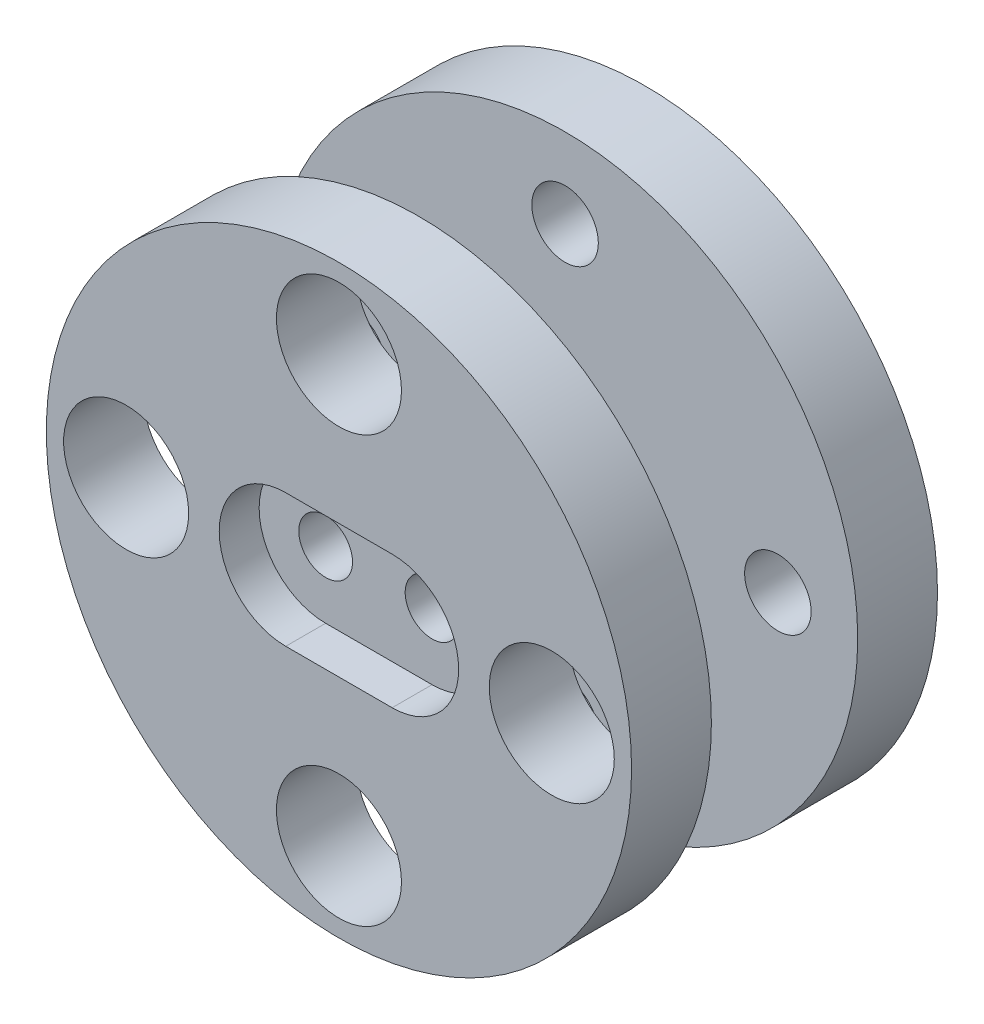
SolidWorks part; units mm, degrees
ref_plane "正面" through (0, 0, 0) normal (0, 0, 1) x (1, 0, 0)
ref_plane "平面" through (0, 0, 0) normal (0, 1, 0) x (1, 0, 0)
ref_plane "右側面" through (0, 0, 0) normal (1, 0, 0) x (0, 0, -1)
sketch "ｽｹｯﾁ1" plane through (0, 0, 0) normal (0, 0, 1) x (1, 0, 0)
  line L0 (0, 0) -> (-8, 0) construction
  circle A0 centre (-8, 0) radius 1.25
  circle A1 centre (0, 8) radius 1.25
  circle A2 centre (8, 0) radius 1.25
  circle A3 centre (0, -8) radius 1.25
  circle A4 centre (0, 0) radius 11
  circle A5 centre (0, 0) radius 3 construction
  point P13 (0, 0)
  dimension "D1" = 2.5
  dimension "D4" = 22
  dimension "D5" = 6
  dimension "D2" = 8
  dimension "D3" = 4
extrude "ﾎﾞｽ - 押し出し1" add sketch "ｽｹｯﾁ1" along normal blind 3
sketch "ｽｹｯﾁ2" plane through (0, 0, 3) normal (0, 0, 1) x (1, 0, 0)
  circle A0 centre (0, 0) radius 3
  dimension "D1" = 6
extrude "ﾎﾞｽ - 押し出し2" add sketch "ｽｹｯﾁ2" along normal blind 5.5 separate body
sketch "ｽｹｯﾁ3" plane through (0, 0, 8.5) normal (0, 0, 1) x (1, 0, 0)
  circle A1 centre (0, 0) radius 11
  circle A2 centre (0, 0) radius 11
  circle A10 centre (-8, 0) radius 2.35
  circle A11 centre (0, 8) radius 2.35
  circle A12 centre (8, 0) radius 2.35
  circle A13 centre (0, -8) radius 2.35
  point P5 (10.1051, 0.0947)
  point P6 (0, 0)
  point P14 (0, 0)
  dimension "D2" = 4.7
  dimension "D1" = 0
  dimension "D3" = 4
extrude "ﾎﾞｽ - 押し出し3" add sketch "ｽｹｯﾁ3" along normal blind 3 separate body
sketch "ｽｹｯﾁ8" plane through (0, 0, 11.5) normal (0, 0, 1) x (1, 0, 0)
  line L0 (0, 3) -> (0, 0) construction
  line L1 (0, 0) -> (-2, 0) construction
  circle A0 centre (0, 0) radius 3 construction
  circle A1 centre (-2, 0) radius 1.01
  circle A2 centre (2, 0) radius 1.01
  dimension "D1" = 6
  dimension "D2" = 2
  dimension "D3" = 2.02
extrude "ｶｯﾄ - 押し出し4" cut sketch "ｽｹｯﾁ8" against normal up to surface (8.5 mm away)
sketch "ｽｹｯﾁ9" plane through (0, 0, 3) normal (0, 0, 1) x (1, 0, 0)
  circle A0 centre (-2, 0) radius 0.8
  circle A1 centre (2, 0) radius 0.8
  dimension "D1" = 1.6
extrude "ｶｯﾄ - 押し出し5" cut sketch "ｽｹｯﾁ9" against normal up to surface (3 mm away) up to face at (11, 0, 0)
sketch "ｽｹｯﾁ11" plane through (0, 0, 11.5) normal (0, 0, 1) x (1, 0, 0)
  line L0 (-2, 0) -> (2, 0) construction
  line L1 (-2, 2.5) -> (2, 2.5)
  line L2 (-2, -2.5) -> (2, -2.5)
  arc A0 (-2, 2.5) -> (-2, -2.5) centre (-2, 0) ccw
  arc A1 (2, -2.5) -> (2, 2.5) centre (2, 0) ccw
  point P4 (0, 0)
  dimension "D1" = 2.5
extrude "ｶｯﾄ - 押し出し6" cut sketch "ｽｹｯﾁ11" against normal offset from surface (1.5 mm away) 10 up to face at (-1.2, 0, 0)
